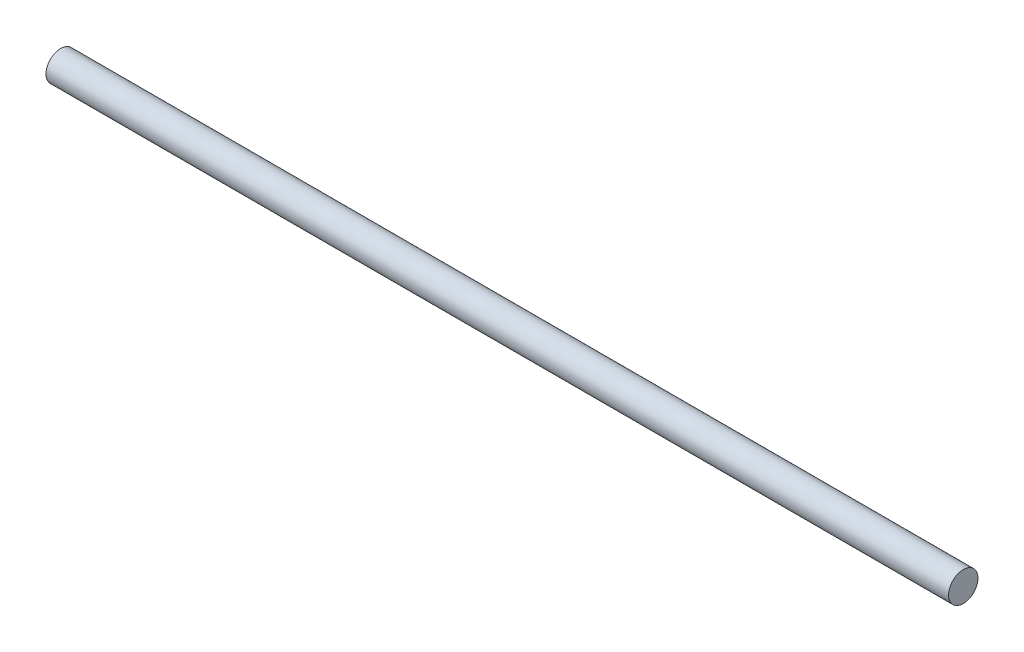
SolidWorks part; units mm, degrees
ref_plane "Front Plane" through (0, 0, 0) normal (0, 0, 1) x (1, 0, 0)
ref_plane "Top Plane" through (0, 0, 0) normal (0, 1, 0) x (1, 0, 0)
ref_plane "Right Plane" through (0, 0, 0) normal (1, 0, 0) x (0, 0, -1)
sketch "Sketch1" plane through (0, 0, 0) normal (1, 0, 0) x (0, 0, -1)
  circle A0 centre (0, 0) radius 45
  dimension "D1" = 90
extrude "Boss-Extrude1" add sketch "Sketch1" along normal blind 2760
